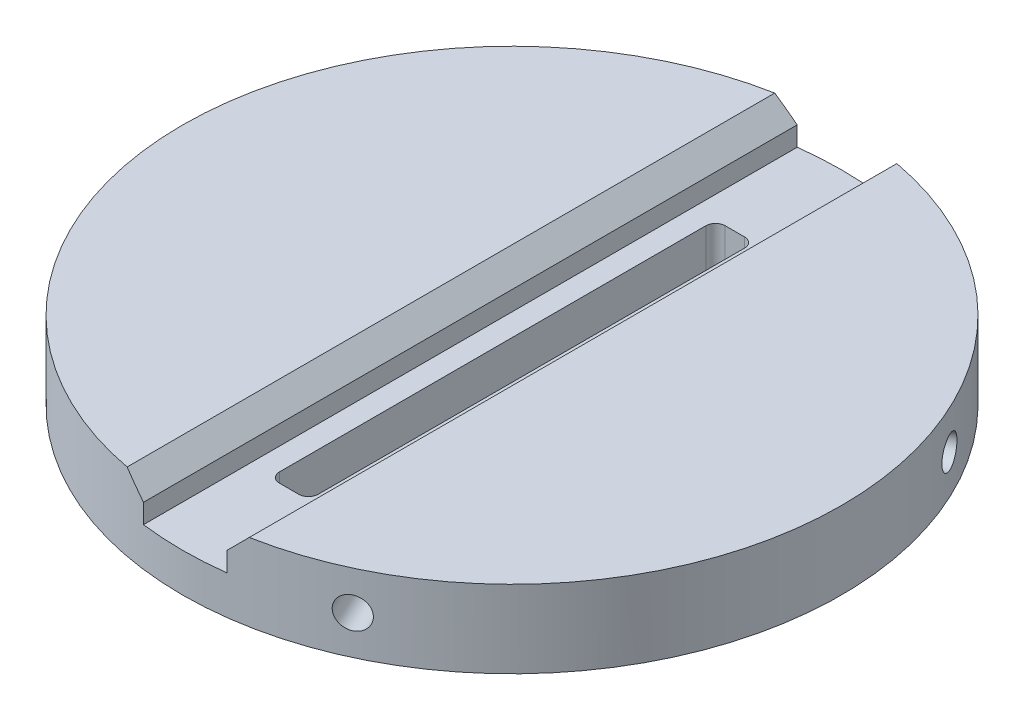
SolidWorks part; units mm, degrees
material "Brass"
ref_plane "Front Plane" through (0, 0, 0) normal (0, 0, 1) x (1, 0, 0)
ref_plane "Top Plane" through (0, 0, 0) normal (0, 1, 0) x (1, 0, 0)
ref_plane "Right Plane" through (0, 0, 0) normal (1, 0, 0) x (0, 0, -1)
sketch "Sketch1" plane through (0, 0, 0) normal (0, 1, 0) x (1, 0, 0)
  circle A0 centre (0, 0) radius 17
  dimension "D1" = 34
extrude "Boss-Extrude1" add sketch "Sketch1" along normal blind 4
sketch "Sketch23" plane through (0, 4, 0) normal (0, 1, 0) x (1, 0, 0)
  line L0 (2.15, 17.8255) -> (2.15, -18.1745)
  line L1 (-2.15, -18.1745) -> (2.15, -18.1745)
  line L2 (-2.15, 17.8255) -> (-2.15, -18.1745)
  line L3 (-2.15, 17.8255) -> (2.15, 17.8255)
  point P6 (0, 0)
  point P7 (0, 0)
  point P27 (0, 0)
  dimension "D1" = 36
  dimension "D2" = 4.3
extrude "Cut-Extrude5" cut sketch "Sketch23" against normal blind 2
sketch "Sketch24" plane through (0, 2, 0) normal (0, 1, 0) x (1, 0, 0)
  line L1 (-1, -11.5) -> (1, -11.5)
  line L2 (-1, -11.5) -> (-1, 11.5)
  line L3 (-1, 11.5) -> (1, 11.5)
  line L4 (1, -11.5) -> (1, 11.5)
  point P0 (0, 0)
  dimension "D1" = 23
  dimension "D2" = 2
  dimension "D3" = 11.5
extrude "Cut-Extrude6" cut sketch "Sketch24" against normal through all
fillet "Fillet4" radius 0.5 4 edges at (-1, 1, 11.5) (1, 1, 11.5) (-1, 1, -11.5) (1, 1, -11.5)
chamfer "Chamfer1" distance 1 angle 45 2 edges at (2.15, 4, 0) (-2.15, 4, 0)
sketch "Sketch26" plane through (0, 2, 0) normal (0, -1, 0) x (1, 0, 0)
  line L0 (0, 0) -> (0, -17)
  line L1 (0, 0) -> (-7.1845, -15.4072)
  circle A0 centre (0, 0) radius 17 construction
  dimension "D1" = 25
hole_wizard "M2 Tapped Hole1" positions "3DSketch1" profile "Sketch27" tap size "M2" standard "DIN"
sketch3d "3DSketch1"
  point P0 (-7.1845, 2, -15.4072)
sketch "Sketch27" plane through (-7.1845, 2, -15.4072) normal (0, 1, 0) x (-0.9063, 0, 0.4226)
  line L0 (0, 0) -> (0, 5.6807)
  line L1 (0, 5.6807) -> (0.8, 5.2)
  line L2 (0.8, 5.2) -> (0.8, 0)
  line L5 (0.8, 0) -> (0, 0)
  line L10 (0, 5.6807) -> (-0.8, 5.2) construction
  line L11 (0, -6.35) -> (0, 107.95) construction
  dimension "Tap Drill Dia." = 1.6
  dimension "Tap Drill Depth" = 5.2
  dimension "Drill Angle" = 118
cosmetic thread "Hole Thread1" parameters "D1"=4, "D2"=2
pattern_circular "CirPattern1" count 4 over 360 of "M2 Tapped Hole1"
